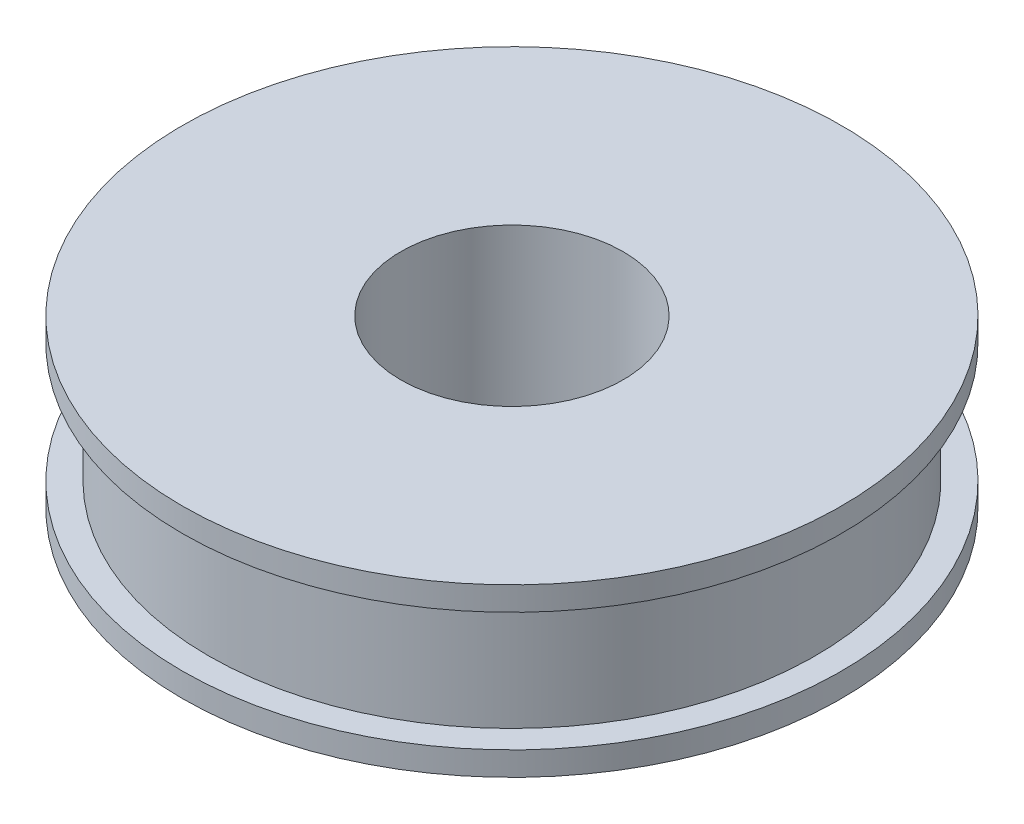
SolidWorks part; units mm, degrees
ref_plane "Front Plane" through (0, 0, 0) normal (0, 0, 1) x (1, 0, 0)
ref_plane "Top Plane" through (0, 0, 0) normal (0, 1, 0) x (1, 0, 0)
ref_plane "Right Plane" through (0, 0, 0) normal (1, 0, 0) x (0, 0, -1)
sketch "Sketch1" plane through (0, 0, 0) normal (0, 1, 0) x (1, 0, 0)
  circle A0 centre (0, 0) radius 14
  circle A1 centre (0, 0) radius 41.5
  dimension "D1" = 83
  dimension "D2" = 28
extrude "Boss-Extrude1" add sketch "Sketch1" along normal blind 3
sketch "Sketch2" plane through (0, 3, 0) normal (0, 1, 0) x (1, 0, 0)
  circle A0 centre (0, 0) radius 14
  circle A1 centre (0, 0) radius 38.195
  dimension "D1" = 76.39
  dimension "D2" = 28
extrude "Boss-Extrude2" add sketch "Sketch2" along normal blind 15
sketch "Sketch3" plane through (0, 18, 0) normal (0, 1, 0) x (1, 0, 0)
  circle A0 centre (0, 0) radius 14
  circle A1 centre (0, 0) radius 41.5
  dimension "D1" = 28
  dimension "D2" = 83
extrude "Boss-Extrude3" add sketch "Sketch3" along normal blind 3
